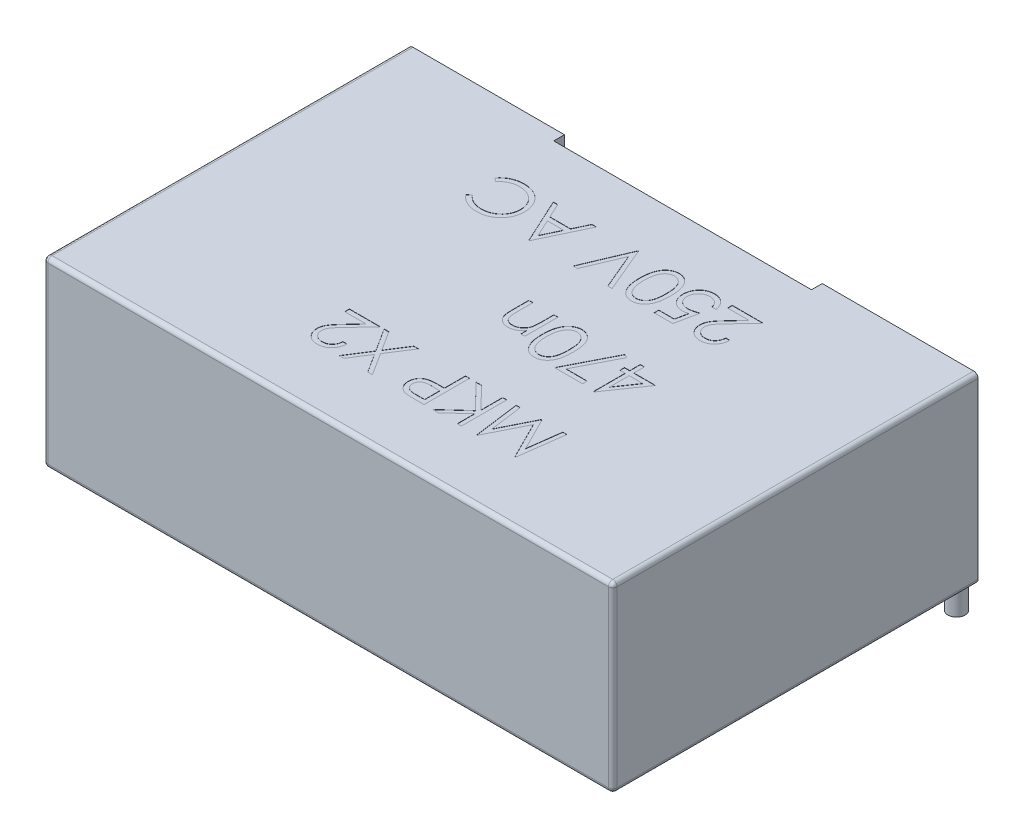
SolidWorks part; units mm, degrees
material "Duranickel(R) 301"
ref_plane "Front Plane" through (0, 0, 0) normal (0, 0, 1) x (1, 0, 0)
ref_plane "Top Plane" through (0, 0, 0) normal (0, 1, 0) x (1, 0, 0)
ref_plane "Right Plane" through (0, 0, 0) normal (1, 0, 0) x (0, 0, -1)
sketch "Sketch1" plane through (0, 0, 0) normal (0, 0, 1) x (1, 0, 0)
  line L0 (-13.25, 8.5) -> (13.25, 0) construction
  line L1 (-13.25, 0) -> (13.25, 0)
  line L2 (-13.25, 0) -> (-13.25, 8.5)
  line L3 (-13.25, 8.5) -> (13.25, 8.5)
  line L4 (13.25, 0) -> (13.25, 8.5)
  line L5 (-13.25, 0) -> (13.25, 8.5) construction
  dimension "D1" = 26.5
  dimension "D2" = 8.5
extrude "Extrude1" add sketch "Sketch1" along normal blind 17
fillet "Fillet1" radius 0.2 8 edges at (0, 8.5, 17) (13.25, 8.5, 8.5) (13.25, 0, 8.5) (13.25, 4.25, 17) (0, 0, 17) (-13.25, 8.5, 8.5) (-13.25, 4.25, 17) (-13.25, 0, 8.5)
sketch "Sketch3" plane through (0, 8.5, 0) normal (0, -1, 0) x (1, 0, 0)
  text T0 "MKP X2\r\n470n\r\n250V AC" font "Century Gothic" height in points 8
extrude "Cut-Extrude1" cut sketch "Sketch3" along normal blind 0.01
ref_plane "Plane2" through (11.25, 0, 0) normal (1, 0, 0) x (0, 0, -1)
sketch "Sketch4" plane through (11.25, 0, 0) normal (1, 0, 0) x (0, 0, -1)
  line L0 (0, 4.25) -> (0.2, 4.25)
  line L1 (0, 0.2) -> (0, 8.3) construction
  line L2 (1, 3.45) -> (1, -2.54)
  arc A0 (0.2, 4.25) -> (1, 3.45) centre (0.2, 3.45) cw
  point P8 (1, 4.25)
  dimension "D3" = 0.8
  dimension "D1" = 1
  dimension "D2" = 2.54
ref_plane "Plane3" through (0, -2.54, 0) normal (0, 1, 0) x (1, 0, 0)
sketch "Sketch5" plane through (0, -2.54, 0) normal (0, 1, 0) x (1, 0, 0)
  circle A0 centre (11.25, 1) radius 0.4
sweep "Sweep1" add profiles "Sketch5" path "Sketch4"
mirror "Mirror2" about plane through (0, 0, 0) normal (1, 0, 0) of "Sweep1"
sketch "Sketch6" plane through (0, 0, 0) normal (0, 0, -1) x (-1, 0, 0)
  line L1 (13.05, 0) -> (-13.05, 0) construction
  line L2 (-6, 8.5) -> (6, 8.5)
  line L3 (-6, 8.5) -> (-6, 0)
  line L4 (-6, 0) -> (6, 0)
  line L6 (6, 8.5) -> (6, 0)
  line L7 (-6, 8.5) -> (6, 0) construction
  line L8 (-6, 0) -> (6, 8.5) construction
  point P0 (0, 4.25)
  dimension "D1" = 12
extrude "Cut-Extrude2" cut sketch "Sketch6" against normal blind 0.5
sketch "Sketch7" plane through (0, 0, 0) normal (0, 0, -1) x (-1, 0, 0)
  line L0 (-13.25, 0.2) -> (-13.25, 8.3) construction
  line L1 (-12.75, 8) -> (12.75, 8)
  line L2 (-12.75, 8) -> (-12.75, 0.4368)
  line L3 (-12.75, 0.4368) -> (12.75, 0.4368)
  line L4 (12.75, 8) -> (12.75, 0.4368)
  line L5 (-12.75, 8) -> (12.75, 0.4368) construction
  line L6 (-12.75, 0.4368) -> (12.75, 8) construction
  line L7 (-13.05, 8.5) -> (-6, 8.5) construction
  point P0 (0, 4.2184)
  dimension "D1" = 0.5
  dimension "D2" = 0.5
extrude "Cut-Extrude4" cut sketch "Sketch7" against normal blind 0.6
